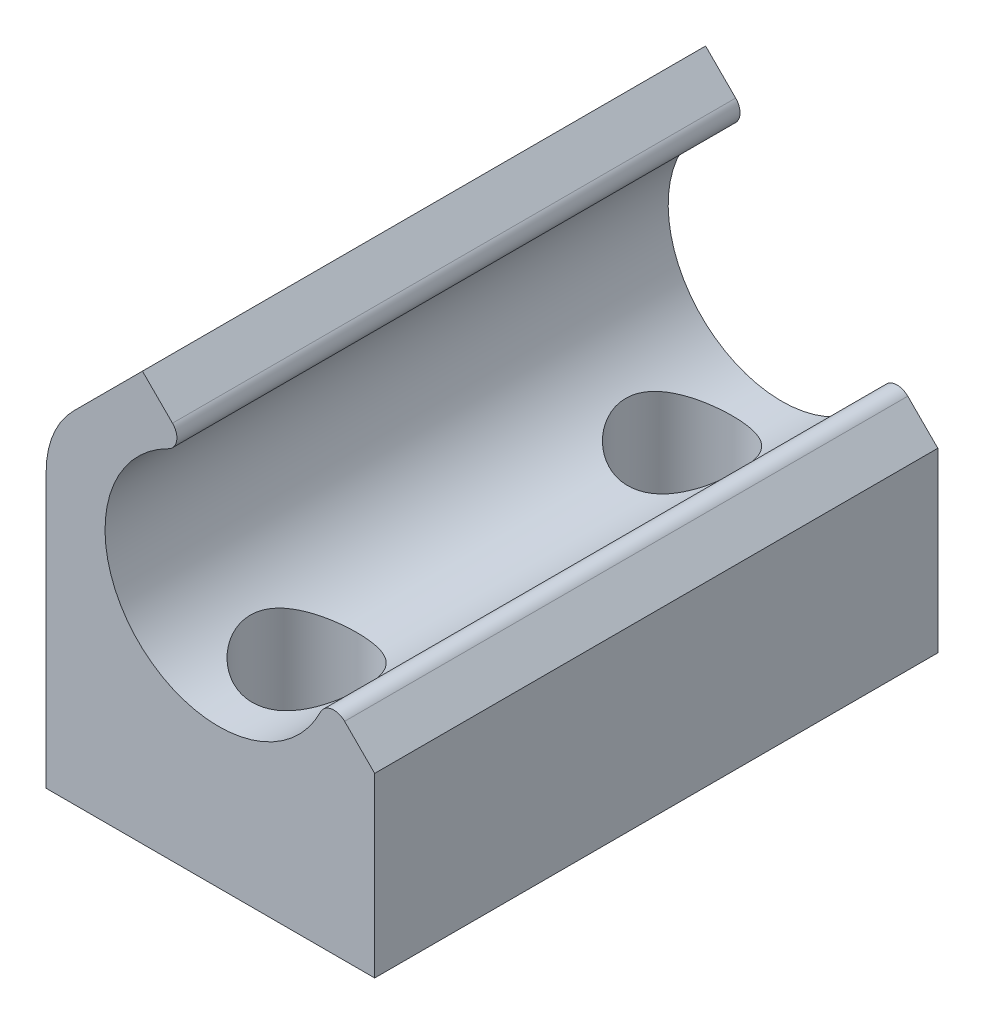
SolidWorks part; units mm, degrees
ref_plane "Front Plane" through (0, 0, 0) normal (0, 0, 1) x (1, 0, 0)
ref_plane "Top Plane" through (0, 0, 0) normal (0, 1, 0) x (1, 0, 0)
ref_plane "Right Plane" through (0, 0, 0) normal (1, 0, 0) x (0, 0, -1)
sketch "Sketch1" plane through (0, 0, 0) normal (0, 0, 1) x (1, 0, 0)
  line L0 (0, 0) -> (17.5, 0)
  line L1 (17.5, 0) -> (17.5, 9.44)
  line L2 (17.5, 9.44) -> (15.0251, 11.9149)
  line L3 (7.6032, 19.3368) -> (5.1283, 21.8117)
  line L4 (5.1283, 21.8117) -> (0, 16.6833)
  line L5 (0, 16.6833) -> (0, 0)
  arc A0 (15.0251, 11.9149) -> (7.6032, 19.3368) centre (9.1858, 13.4974) cw
  dimension "D1" = 6.05
  dimension "D2" = 3.5
  dimension "D3" = 17.5
  dimension "D4" = 9.44
  dimension "D5" = 3.01
  dimension "D6" = 45
extrude "Boss-Extrude1" add sketch "Sketch1" along normal blind 30
fillet "Fillet1" radius 0.8 2 edges at (15.0251, 11.9149, 15) (7.6032, 19.3368, 15)
ref_plane "Plane1" through (0, 10.8284, 0) normal (0, -1, 0) x (-1, 0, 0)
sketch "Sketch3" plane through (0, 10.8284, 0) normal (0, -1, 0) x (-1, 0, 0)
  line L0 (-3.1358, 0) -> (-14.6152, 0) construction
  line L1 (-3.1358, 0) -> (-14.6152, 0) construction
  circle A0 centre (-8.8755, -5) radius 3
  circle A1 centre (-8.8755, -25) radius 3
  point P7 (-8.8755, 0)
  dimension "D1" = 6
  dimension "D2" = 5
  dimension "D3" = 20
extrude "Cut-Extrude1" cut sketch "Sketch3" along normal blind 9
sketch "Sketch4" plane through (0, 10.8284, 0) normal (0, -1, 0) x (-1, 0, 0)
  circle A0 centre (-8.8755, -5) radius 1.55
  circle A1 centre (-8.8755, -25) radius 1.55
  dimension "D1" = 3.1
  dimension "D2" = 3.1
extrude "Cut-Extrude2" cut sketch "Sketch4" along normal through all
fillet "Fillet2" radius 5 1 edges at (0, 16.6833, 15)
